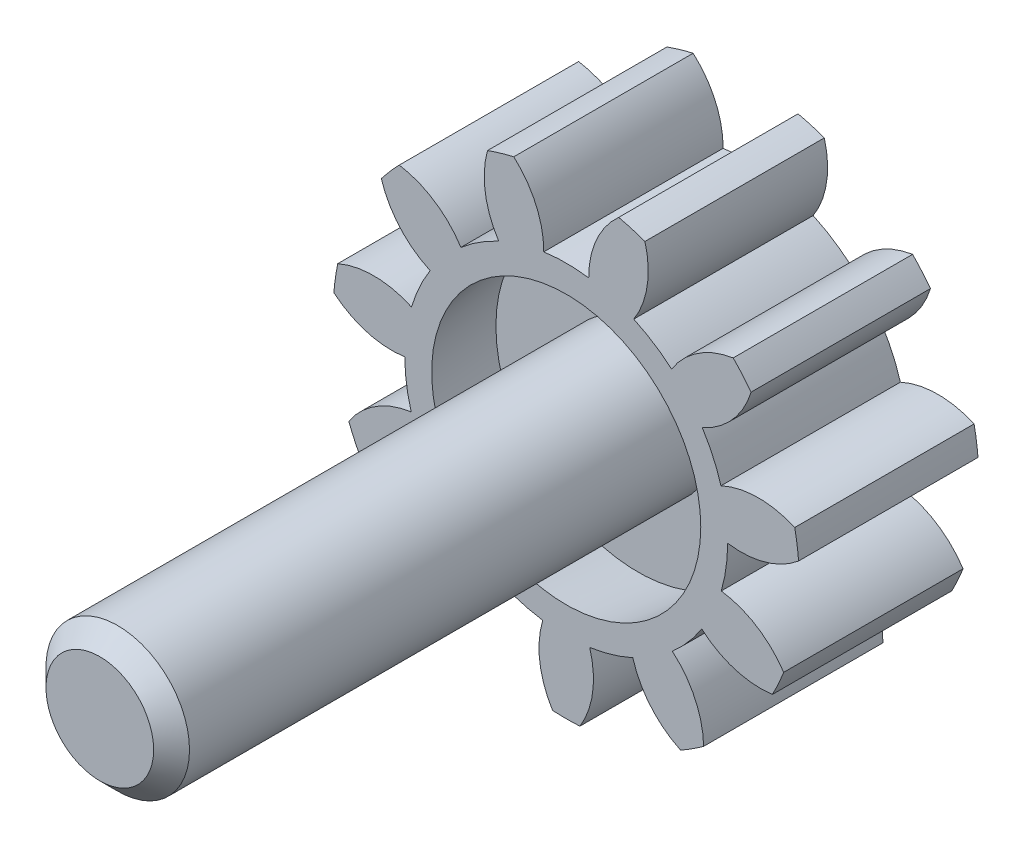
SolidWorks part; units mm, degrees
ref_plane "Спереди" through (0, 0, 0) normal (0, 0, 1) x (1, 0, 0)
ref_plane "Сверху" through (0, 0, 0) normal (0, 1, 0) x (1, 0, 0)
ref_plane "Справа" through (0, 0, 0) normal (1, 0, 0) x (0, 0, -1)
sketch "Эскиз1" plane through (0, 0, 0) normal (0, 0, 1) x (1, 0, 0)
  circle A0 centre (0, 0) radius 13
  dimension "D1" = 26
extrude "Бобышка-Вытянуть2" add sketch "Эскиз1" against normal blind 10
sketch "Эскиз2" plane through (0, 0, 0) normal (0, 0, 1) x (1, 0, 0)
  line L0 (0, 0) -> (0, 19.6211) construction
  line L1 (0, 0) -> (-2.6728, 19.0179) construction
  line L2 (0, 0) -> (-4.2994, 18.6227) construction
  arc A0 (1.2526, 8.9124) -> (-1.2526, 8.9124) centre (0, 0) ccw
  arc A1 (2.9244, 12.6668) -> (-2.9244, 12.6668) centre (0, 0) ccw
  circle A2 centre (0, 0) radius 13 construction
  arc A3 (-2.9244, 12.6668) -> (-1.2526, 8.9124) centre (-6.2525, 8.9354) cw
  arc A4 (2.9244, 12.6668) -> (1.2526, 8.9124) centre (6.2525, 8.9354) ccw
  arc A5 (9.3083, 9.075) -> (4.3881, 12.237) centre (0, 0) ccw
  arc A6 (4.3881, 12.237) -> (3.7647, 8.1748) centre (-0.4291, 10.8973) cw
  arc A7 (5.8721, 6.8204) -> (3.7647, 8.1748) centre (0, 0) ccw
  arc A8 (9.3083, 9.075) -> (5.8721, 6.8204) centre (10.0908, 4.1366) ccw
  arc A9 (12.737, 2.6019) -> (10.3073, 7.9221) centre (0, 0) ccw
  arc A10 (10.3073, 7.9221) -> (7.5867, 4.8417) centre (5.5305, 9.3994) cw
  arc A11 (8.6273, 2.563) -> (7.5867, 4.8417) centre (0, 0) ccw
  arc A12 (12.737, 2.6019) -> (8.6273, 2.563) centre (10.7253, -1.9756) ccw
  arc A13 (12.1217, -4.6973) -> (12.9541, 1.0919) centre (0, 0) ccw
  arc A14 (12.9541, 1.0919) -> (9, -0.0286) centre (9.7343, 4.9172) cw
  arc A15 (8.6434, -2.5082) -> (9, -0.0286) centre (0, 0) ccw
  arc A16 (12.1217, -4.6973) -> (8.6434, -2.5082) centre (7.9546, -7.4605) ccw
  arc A17 (7.6579, -10.5051) -> (11.488, -6.0849) centre (0, 0) ccw
  arc A18 (11.488, -6.0849) -> (7.5558, -4.8898) centre (10.8474, -1.1261) cw
  arc A19 (5.9153, -6.783) -> (7.5558, -4.8898) centre (0, 0) ccw
  arc A20 (7.6579, -10.5051) -> (5.9153, -6.783) centre (2.6584, -10.5768) ccw
  arc A21 (0.7627, -12.9776) -> (6.3746, -11.3298) centre (0, 0) ccw
  arc A22 (6.3746, -11.3298) -> (3.7127, -8.1985) centre (8.5166, -6.8119) cw
  arc A23 (1.3091, -8.9043) -> (3.7127, -8.1985) centre (0, 0) ccw
  arc A24 (0.7627, -12.9776) -> (1.3091, -8.9043) centre (-3.4818, -10.335) ccw
  arc A25 (-6.3746, -11.3298) -> (-0.7627, -12.9776) centre (0, 0) ccw
  arc A26 (-0.7627, -12.9776) -> (-1.3091, -8.9043) centre (3.4818, -10.335) cw
  arc A27 (-3.7127, -8.1985) -> (-1.3091, -8.9043) centre (0, 0) ccw
  arc A28 (-6.3746, -11.3298) -> (-3.7127, -8.1985) centre (-8.5166, -6.8119) ccw
  arc A29 (-11.488, -6.0849) -> (-7.6579, -10.5051) centre (0, 0) ccw
  arc A30 (-7.6579, -10.5051) -> (-5.9153, -6.783) centre (-2.6584, -10.5768) cw
  arc A31 (-7.5558, -4.8898) -> (-5.9153, -6.783) centre (0, 0) ccw
  arc A32 (-11.488, -6.0849) -> (-7.5558, -4.8898) centre (-10.8474, -1.1261) ccw
  arc A33 (-12.9541, 1.0919) -> (-12.1217, -4.6973) centre (0, 0) ccw
  arc A34 (-12.1217, -4.6973) -> (-8.6434, -2.5082) centre (-7.9546, -7.4605) cw
  arc A35 (-9, -0.0286) -> (-8.6434, -2.5082) centre (0, 0) ccw
  arc A36 (-12.9541, 1.0919) -> (-9, -0.0286) centre (-9.7343, 4.9172) ccw
  arc A37 (-10.3073, 7.9221) -> (-12.737, 2.6019) centre (0, 0) ccw
  arc A38 (-12.737, 2.6019) -> (-8.6273, 2.563) centre (-10.7253, -1.9756) cw
  arc A39 (-7.5867, 4.8417) -> (-8.6273, 2.563) centre (0, 0) ccw
  arc A40 (-10.3073, 7.9221) -> (-7.5867, 4.8417) centre (-5.5305, 9.3994) ccw
  arc A41 (-4.3881, 12.237) -> (-9.3083, 9.075) centre (0, 0) ccw
  arc A42 (-9.3083, 9.075) -> (-5.8721, 6.8204) centre (-10.0908, 4.1366) cw
  arc A43 (-3.7647, 8.1748) -> (-5.8721, 6.8204) centre (0, 0) ccw
  arc A44 (-4.3881, 12.237) -> (-3.7647, 8.1748) centre (0.4291, 10.8973) ccw
  dimension "D3" = 9
  dimension "D4" = 5
  dimension "D1" = 8
  dimension "D2" = 13
  dimension "D5" = 11
extrude "Вырез-Вытянуть1" cut sketch "Эскиз2" against normal through all
sketch "Эскиз3" plane through (0, 0, 0) normal (0, 0, 1) x (1, 0, 0)
  circle A0 centre (0, 0) radius 7.5
  dimension "D1" = 15
extrude "Вырез-Вытянуть2" cut sketch "Эскиз3" against normal blind 4 draft 6 draft outward yes
sketch "Эскиз4" plane through (0, 0, -10) normal (0, 0, -1) x (-1, 0, 0)
  circle A0 centre (0, 0) radius 7.5
  dimension "D1" = 15
extrude "Вырез-Вытянуть3" cut sketch "Эскиз4" against normal blind 4 draft 6 draft outward yes
sketch "Эскиз5" plane through (0, 0, -4) normal (0, 0, 1) x (1, 0, 0)
  circle A0 centre (0, 0) radius 4
  circle A1 centre (0, 0) radius 7.9204 construction
  dimension "D1" = 8
extrude "Бобышка-Вытянуть3" add sketch "Эскиз5" along normal blind 30
chamfer "Фаска1" distance 1 angle 45 1 edges at (4, 0, 26)
